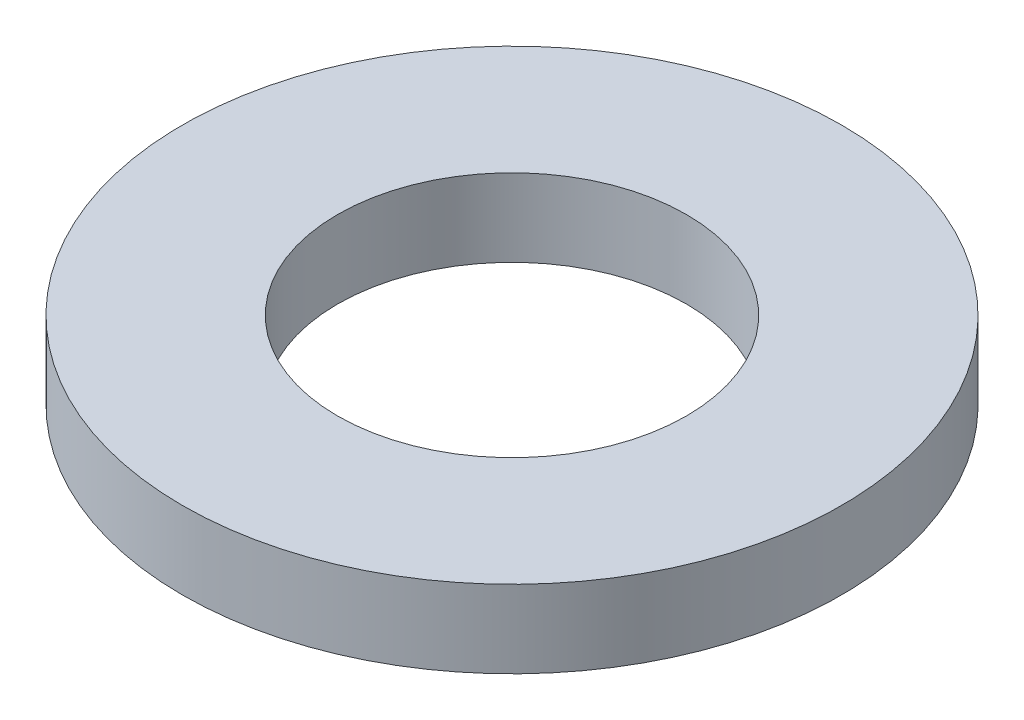
SolidWorks part; units mm, degrees
ref_plane "Front Plane" through (0, 0, 0) normal (0, 0, 1) x (1, 0, 0)
ref_plane "Top Plane" through (0, 0, 0) normal (0, 1, 0) x (1, 0, 0)
ref_plane "Right Plane" through (0, 0, 0) normal (1, 0, 0) x (0, 0, -1)
sketch "Sketch1" plane through (0, 0, 0) normal (0, 1, 0) x (1, 0, 0)
  circle A0 centre (0, 0) radius 28.575
  circle A1 centre (0, 0) radius 53.975
  dimension "D1" = 25.4
  dimension "D2" = 57.15
extrude "Boss-Extrude1" add sketch "Sketch1" along normal blind 12.7
sketch "Sketch2" plane through (0, 12.7, 0) normal (0, 1, 0) x (1, 0, 0)
  line L1 (-63.2766, 57.9831) -> (60.3221, 57.9831)
  line L2 (-63.2766, 57.9831) -> (-63.2766, -62.1687)
  line L3 (-63.2766, -62.1687) -> (60.3221, -62.1687)
  line L4 (60.3221, 57.9831) -> (60.3221, -62.1687)
